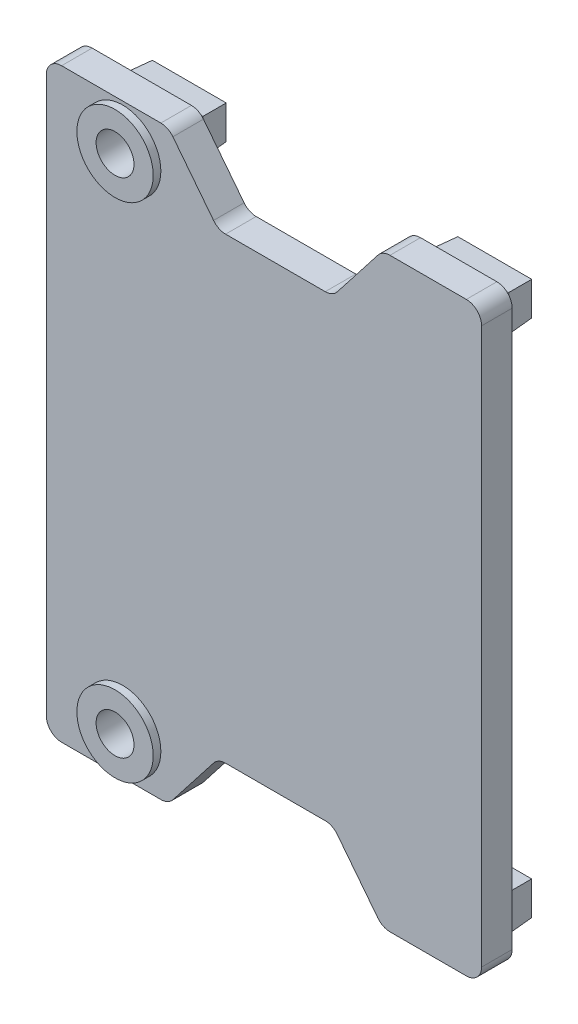
SolidWorks part; units mm, degrees
ref_plane "Front Plane" through (0, 0, 0) normal (0, 0, 1) x (1, 0, 0)
ref_plane "Top Plane" through (0, 0, 0) normal (0, 1, 0) x (1, 0, 0)
ref_plane "Right Plane" through (0, 0, 0) normal (1, 0, 0) x (0, 0, -1)
sketch "Sketch1" plane through (0, 0, 0) normal (0, 0, 1) x (1, 0, 0)
  line L0 (190.5, 35.0834) -> (-190.5, -35.0834) construction
  line L1 (190.5, -31.75) -> (-190.5, -31.75) construction
  line L2 (190.5, -31.75) -> (190.5, 31.75) construction
  line L3 (190.5, 31.75) -> (-190.5, 31.75) construction
  line L4 (-190.5, -31.75) -> (-190.5, 23.09) construction
  line L5 (190.5, -31.75) -> (-190.5, 31.75) construction
  line L6 (190.5, 31.75) -> (-190.5, -31.75) construction
  line L7 (-190.5, 26.44) -> (190.5, 26.44) construction
  line L8 (-184.15, 24.36) -> (-180.975, 24.36)
  line L9 (178.0459, 19.05) -> (-197.2145, 19.05) construction
  line L10 (-179.9737, 23.8712) -> (-176.5938, 19.5388)
  line L11 (-166.3062, 19.5388) -> (-162.9263, 23.8712)
  line L12 (-161.925, 24.36) -> (-155.575, 24.36)
  line L13 (-154.305, 23.09) -> (-154.305, 0)
  line L14 (0, 0) -> (-190.5, 0) construction
  line L15 (-154.305, 0) -> (-190.5, 0)
  line L16 (-190.5, 0) -> (-190.5, 23.09)
  line L17 (-175.5925, 19.05) -> (-167.3075, 19.05)
  line L18 (-184.15, 24.36) -> (-189.23, 24.36)
  line L19 (-155.575, 23.09) -> (-161.925, 23.09) construction
  line L20 (-155.575, 23.09) -> (-155.575, 20.09) construction
  line L21 (-155.575, 20.09) -> (-161.925, 20.09) construction
  line L22 (-161.925, 23.09) -> (-161.925, 20.09) construction
  line L23 (-155.575, 23.09) -> (-161.925, 20.09) construction
  line L24 (-155.575, 20.09) -> (-161.925, 23.09) construction
  line L25 (-190.5, 25.4) -> (-190.5, 23.09) construction
  line L26 (-190.5, 23.09) -> (-190.5, 25.4) construction
  line L27 (-180.975, 23.09) -> (-187.325, 23.09) construction
  line L28 (-180.975, 23.09) -> (-180.975, 20.09) construction
  line L29 (-180.975, 20.09) -> (-187.325, 20.09) construction
  line L30 (-187.325, 23.09) -> (-187.325, 20.09) construction
  line L31 (-180.975, 23.09) -> (-187.325, 20.09) construction
  line L32 (-180.975, 20.09) -> (-187.325, 23.09) construction
  line L33 (-190.5, 25.4) -> (-190.5, 31.75) construction
  line L34 (-190.5, 23.09) -> (-190.5, 25.4) construction
  circle A0 centre (-184.15, 20.8964) radius 5.5436 construction
  circle A1 centre (-184.15, 20.8964) radius 4.5 construction
  circle A2 centre (-184.15, 20.8964) radius 1.575
  circle A3 centre (-184.15, 20.8964) radius 3.175 construction
  arc A4 (-175.5925, 19.05) -> (-176.5938, 19.5388) centre (-175.5925, 20.32) cw
  arc A5 (-167.3075, 19.05) -> (-166.3062, 19.5388) centre (-167.3075, 20.32) ccw
  arc A6 (-162.9263, 23.8712) -> (-161.925, 24.36) centre (-161.925, 23.09) cw
  arc A7 (-154.305, 23.09) -> (-155.575, 24.36) centre (-155.575, 23.09) ccw
  arc A8 (-179.9737, 23.8712) -> (-180.975, 24.36) centre (-180.975, 23.09) ccw
  arc A9 (-189.23, 24.36) -> (-190.5, 23.09) centre (-189.23, 23.09) ccw
  point P0 (0, 0)
  point P8 (0, 0)
  point P27 (-158.75, 21.59)
  point P34 (-171.2683, 29.44)
  point P37 (-176.2125, 19.05)
  point P40 (-166.6875, 19.05)
  point P46 (-176.2125, 19.05)
  point P51 (-190.5, 24.36)
  point P52 (0, 0)
  point P53 (-167.5412, 20.09)
  point P54 (-184.15, 21.59)
  point P59 (0, 0)
  point P60 (0, 0)
  point P61 (-171.45, 19.05)
  point P62 (0, 0)
  point P63 (0, 0)
  dimension "D3" = 9
  dimension "D4" = 11.0871
  dimension "D6" = 3.15
  dimension "D7" = 6.35
  dimension "D14" = 1.27
  dimension "D1" = 63.5
  dimension "D2" = 5.31
  dimension "D5" = 6.35
  dimension "D8" = 9.525
  dimension "D9" = 19.05
  dimension "D10" = 3
  dimension "D11" = 6.35
  dimension "D12" = 21.59
  dimension "D13" = 31.75
  dimension "D15" = 6.35
  dimension "D16" = 6.35
  dimension "D17" = 3
  dimension "D18" = 381
  dimension "D21" = 19.05
extrude "Boss-Extrude1" add sketch "Sketch1" along normal blind 2.54
sketch "Sketch2" plane through (0, 0, 2.54) normal (0, 0, 1) x (1, 0, 0)
  circle A0 centre (-184.15, 20.8964) radius 1.575
  circle A1 centre (-184.15, 20.8964) radius 3.175
  circle A2 centre (-184.15, 20.8964) radius 1.575 construction
  dimension "D1" = 6.35
extrude "Boss-Extrude2" add sketch "Sketch2" along normal offset from surface (0.635 mm away) 3.175 up to face at (-171.8582, 19.219, 0)
sketch "Sketch3" plane through (0, 0, 0) normal (0, 0, -1) x (-1, 0, 0)
  line L0 (0, 0) -> (197.0263, 0) construction
  line L1 (187.325, 20.09) -> (180.975, 20.09)
  line L2 (187.325, 20.09) -> (187.325, 23.09)
  line L3 (187.325, 23.09) -> (180.975, 23.09)
  line L4 (180.975, 20.09) -> (180.975, 23.09)
  line L5 (187.325, 20.09) -> (180.975, 23.09) construction
  line L6 (187.325, 23.09) -> (180.975, 20.09) construction
  line L7 (161.925, 20.09) -> (155.575, 20.09)
  line L8 (161.925, 20.09) -> (161.925, 23.09)
  line L9 (161.925, 23.09) -> (155.575, 23.09)
  line L10 (155.575, 20.09) -> (155.575, 23.09)
  line L11 (161.925, 20.09) -> (155.575, 23.09) construction
  line L12 (161.925, 23.09) -> (155.575, 20.09) construction
  line L13 (-190.5, 25.4) -> (190.5, -25.4) construction
  point P0 (184.15, 21.59)
  point P5 (158.75, 21.59)
  point P10 (0, 0)
  dimension "D1" = 6.35
  dimension "D2" = 3
  dimension "D3" = 21.59
  dimension "D4" = 25.4
  dimension "D5" = 6.35
extrude "Boss-Extrude3" add sketch "Sketch3" along normal blind 1
sketch "Sketch4" plane through (0, 0, -1) normal (0, 0, -1) x (-1, 0, 0)
  line L0 (180.975, 23.09) -> (180.975, 20.09) construction
  line L1 (180.975, 20.09) -> (187.325, 20.09) construction
  line L2 (187.325, 20.09) -> (187.325, 23.09) construction
  line L3 (187.325, 23.09) -> (180.975, 23.09) construction
  line L4 (155.575, 23.09) -> (155.575, 20.09) construction
  line L5 (155.575, 20.09) -> (161.925, 20.09) construction
  line L6 (161.925, 20.09) -> (161.925, 23.09) construction
  line L7 (161.925, 23.09) -> (155.575, 23.09) construction
  line L8 (180.975, 23.09) -> (180.975, 20.09)
  line L9 (180.975, 20.09) -> (187.325, 20.09)
  line L10 (187.325, 20.09) -> (187.325, 23.09)
  line L11 (187.325, 23.09) -> (180.975, 23.09)
  line L12 (155.575, 23.09) -> (155.575, 20.09)
  line L13 (155.575, 20.09) -> (161.925, 20.09)
  line L14 (161.925, 20.09) -> (161.925, 23.09)
  line L15 (161.925, 23.09) -> (155.575, 23.09)
extrude "Boss-Extrude4" add sketch "Sketch4" along normal offset from surface 3 draft 3
mirror "Mirror1" about plane through (0, 0, 0) normal (0, 1, 0) of bodies 105 102
